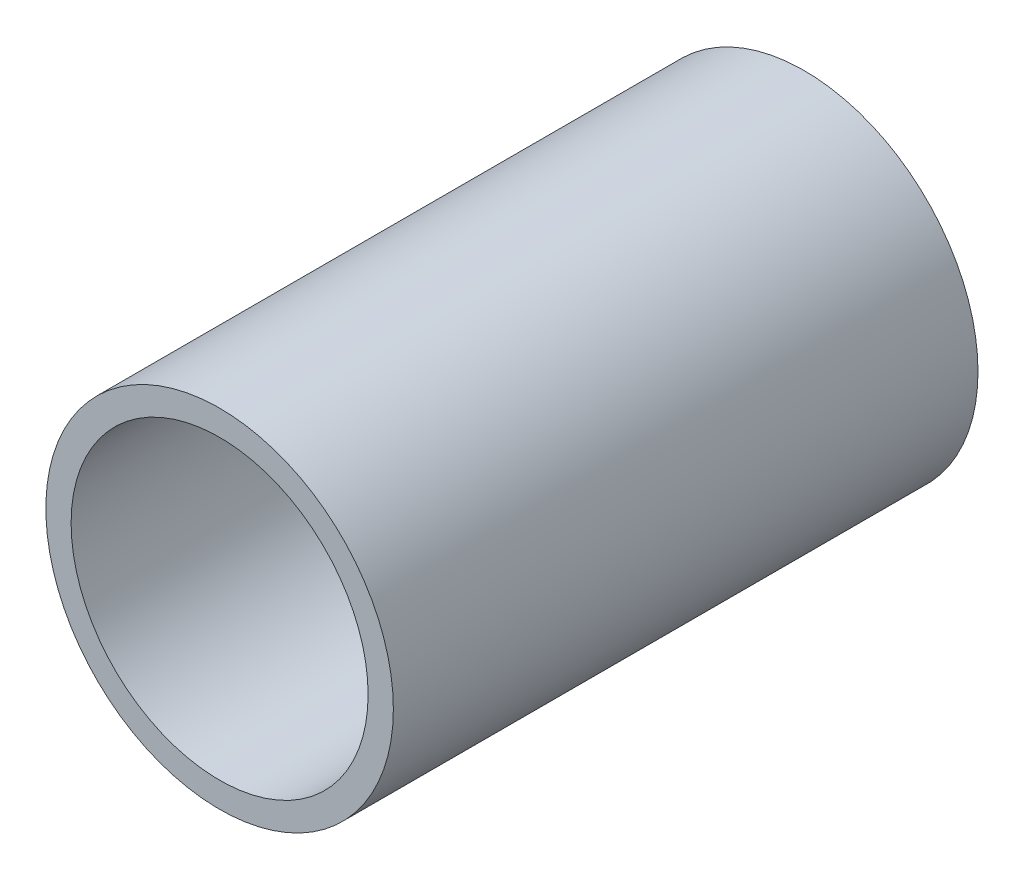
SolidWorks part; units mm, degrees
ref_plane "Alzado" through (0, 0, 0) normal (0, 0, 1) x (1, 0, 0)
ref_plane "Planta" through (0, 0, 0) normal (0, 1, 0) x (1, 0, 0)
ref_plane "Vista lateral" through (0, 0, 0) normal (1, 0, 0) x (0, 0, -1)
sketch "Croquis1" plane through (0, 0, 0) normal (0, 0, 1) x (1, 0, 0)
  circle A0 centre (0, 0) radius 25.4
  circle A1 centre (0, 0) radius 29.72
  dimension "D1" = 59.44
  dimension "D2" = 50.8
extrude "Saliente-Extruir1" add sketch "Croquis1" along normal blind 100
